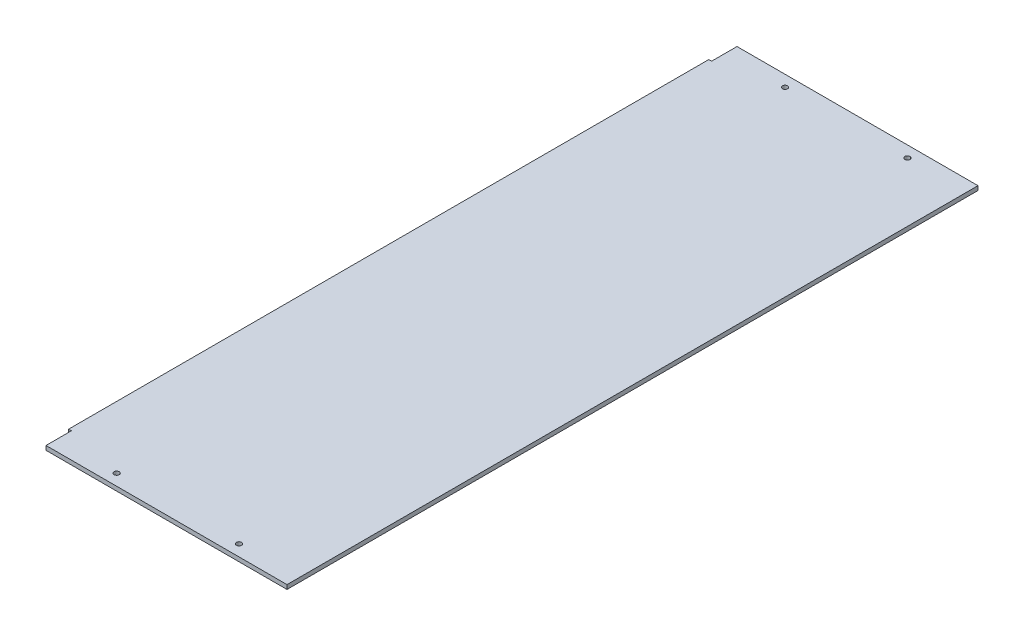
SolidWorks part; units mm, degrees
ref_plane "Front Plane" through (0, 0, 0) normal (0, 0, 1) x (1, 0, 0)
ref_plane "Top Plane" through (0, 0, 0) normal (0, 1, 0) x (1, 0, 0)
ref_plane "Right Plane" through (0, 0, 0) normal (1, 0, 0) x (0, 0, -1)
sketch "Sketch1" plane through (0, 0, 0) normal (0, 1, 0) x (1, 0, 0)
  line L0 (-131, -24) -> (128, -24) construction
  line L1 (-128, 343) -> (128, 343)
  line L2 (-131, 316) -> (-131, -364)
  line L3 (-128, -391) -> (128, -391)
  line L4 (128, 343) -> (128, -391)
  line L7 (-131, 316) -> (-128, 316)
  line L8 (-128, 343) -> (-128, 316)
  line L9 (-131, -364) -> (-128, -364)
  line L10 (-128, -391) -> (-128, -364)
  line L13 (0, 343) -> (0, -391) construction
  circle A0 centre (-65, 331) radius 2.75
  circle A1 centre (65, 331) radius 2.75
  circle A2 centre (65, -379) radius 2.75
  circle A3 centre (-65, -379) radius 2.75
  point P23 (0, 0)
  dimension "D7" = 12
  dimension "D9" = 12
  dimension "D1" = 27
  dimension "D2" = 3
  dimension "D4" = 734
  dimension "D5" = 131
  dimension "D6" = 343
  dimension "D8" = 65
  dimension "D10" = 27
extrude "Boss-Extrude2" add sketch "Sketch1" along normal blind 4.5
